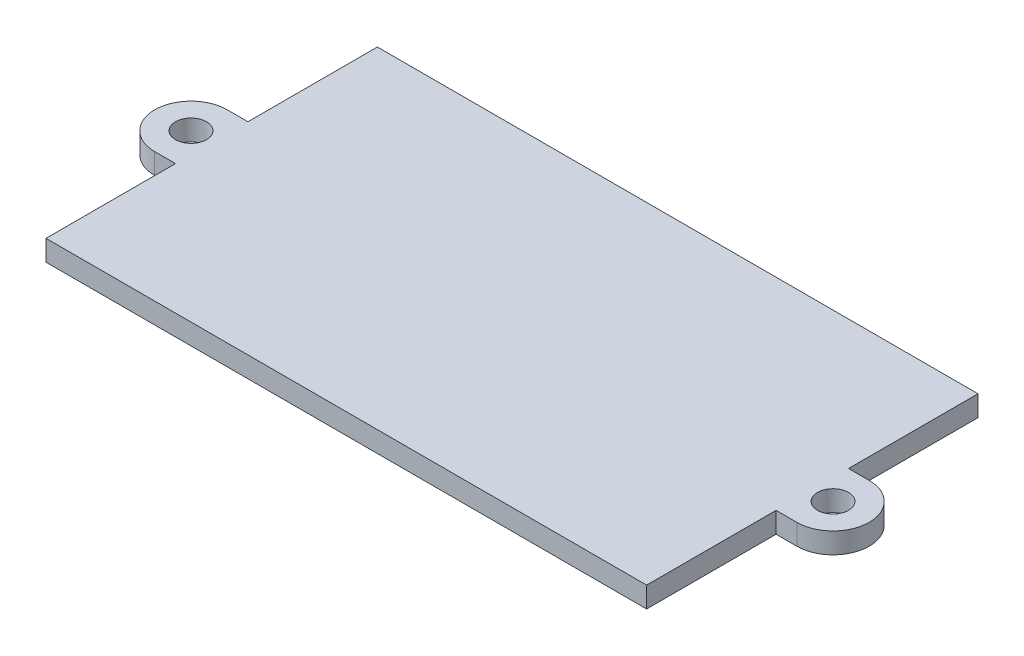
SolidWorks part; units mm, degrees
ref_plane "Alzado" through (0, 0, 0) normal (0, 0, 1) x (1, 0, 0)
ref_plane "Planta" through (0, 0, 0) normal (0, 1, 0) x (1, 0, 0)
ref_plane "Vista lateral" through (0, 0, 0) normal (1, 0, 0) x (0, 0, -1)
sketch "Croquis1" plane through (0, 0, 0) normal (0, 1, 0) x (1, 0, 0)
  line L0 (0, 0) -> (0, 33.566) construction
  line L1 (0, 0) -> (44.3915, 0) construction
  line L2 (-29, 0) -> (-29, 16)
  line L3 (-29, 16) -> (0, 16)
  line L4 (0, 16) -> (29, 16)
  line L5 (29, 16) -> (29, 0)
  line L6 (29, 0) -> (29, -16)
  line L7 (29, -16) -> (0, -16)
  line L8 (0, -16) -> (-29, -16)
  line L9 (-29, -16) -> (-29, 0)
  line L10 (-31, 3.5) -> (-29, 3.5)
  line L11 (-31, -3.5) -> (-29, -3.5)
  line L12 (31, -3.5) -> (29, -3.5)
  line L13 (31, 3.5) -> (29, 3.5)
  circle A0 centre (-31, 0) radius 1.5
  arc A1 (-31, 3.5) -> (-31, -3.5) centre (-31, 0) ccw
  arc A2 (31, 3.5) -> (31, -3.5) centre (31, 0) cw
  circle A3 centre (31, 0) radius 1.5
  point P26 (-34.5, 0)
  dimension "D5" = 2
  dimension "D6" = 5.5
  dimension "D1" = 16
  dimension "D2" = 16
  dimension "D3" = 29
  dimension "D4" = 29
extrude "Saliente-Extruir1" add sketch "Croquis1" along normal blind 2 contours L9 L8 L7 L6 L5 L4 L3 L2 | A2 L13 L5 L6 L12 A3 | L10 A1 L11 L9 L2 A0
